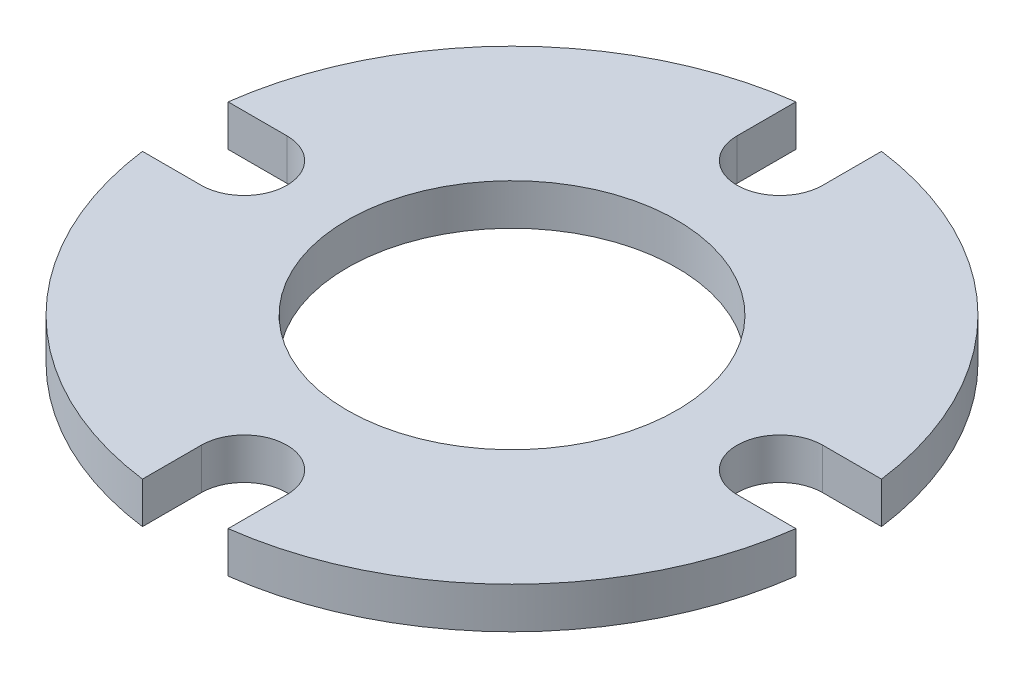
SolidWorks part; units mm, degrees
ref_plane "Front Plane" through (0, 0, 0) normal (0, 0, 1) x (1, 0, 0)
ref_plane "Top Plane" through (0, 0, 0) normal (0, 1, 0) x (1, 0, 0)
ref_plane "Right Plane" through (0, 0, 0) normal (1, 0, 0) x (0, 0, -1)
sketch "Sketch1" plane through (0, 0, 0) normal (0, 1, 0) x (1, 0, 0)
  line L0 (0, 1.2081) -> (0, -1.3078) construction
  line L1 (-1.7076, 0) -> (1.545, 0) construction
  line L2 (0.813, 0.1416) -> (0.813, -0.1416) construction
  line L3 (-0.1914, -0.813) -> (0.1914, -0.813) construction
  line L4 (0.813, 0.13) -> (0.9915, 0.13)
  line L5 (0.813, -0.13) -> (0.9915, -0.13)
  line L6 (-0.13, -0.813) -> (-0.13, -0.9915)
  line L7 (0.13, -0.813) -> (0.13, -0.9915)
  line L8 (-0.813, 0.13) -> (-0.9915, 0.13)
  line L9 (-0.813, -0.13) -> (-0.9915, -0.13)
  line L10 (0.13, 0.813) -> (0.13, 0.9915)
  line L11 (-0.13, 0.813) -> (-0.13, 0.9915)
  arc A0 (-0.13, 0.9915) -> (-0.9915, 0.13) centre (0, 0) ccw
  circle A1 centre (0, 0) radius 0.5
  arc A2 (0.813, 0.13) -> (0.813, -0.13) centre (0.813, 0) ccw
  arc A3 (0.13, -0.813) -> (-0.13, -0.813) centre (0, -0.813) ccw
  arc A4 (-0.813, -0.13) -> (-0.813, 0.13) centre (-0.813, 0) ccw
  arc A5 (-0.13, 0.813) -> (0.13, 0.813) centre (0, 0.813) ccw
  arc A6 (-0.9915, -0.13) -> (-0.13, -0.9915) centre (0, 0) ccw
  arc A7 (0.9915, 0.13) -> (0.13, 0.9915) centre (0, 0) ccw
  arc A8 (0.13, -0.9915) -> (0.9915, -0.13) centre (0, 0) ccw
  point P12 (0, -0.813)
  point P13 (0.813, 0)
  point P14 (0, -0.0499)
  point P26 (0, 0)
  point P43 (0, 0)
  dimension "D1" = 1
  dimension "D2" = 1
  dimension "D5" = 0.26
  dimension "D3" = 0.813
  dimension "D6" = 4
  dimension "D7" = 4
extrude "Boss-Extrude1" add sketch "Sketch1" along normal blind 0.125
